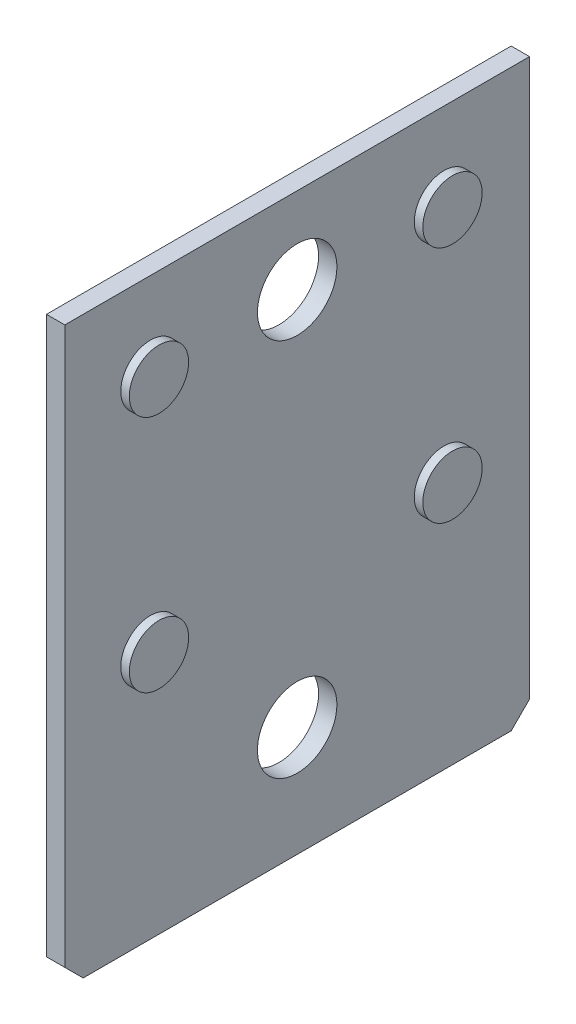
SolidWorks part; units mm, degrees
ref_plane "Front Plane" through (0, 0, 0) normal (0, 0, 1) x (1, 0, 0)
ref_plane "Top Plane" through (0, 0, 0) normal (0, 1, 0) x (1, 0, 0)
ref_plane "Right Plane" through (0, 0, 0) normal (1, 0, 0) x (0, 0, -1)
sketch "Sketch1" plane through (0, 0, 0) normal (1, 0, 0) x (0, 0, -1)
  line L1 (-19, 0) -> (19, 0)
  line L2 (-19, 0) -> (-19, 47)
  line L3 (-19, 47) -> (19, 47)
  line L4 (19, 0) -> (19, 47)
  point P4 (0, 40)
  point P6 (0, -73)
  dimension "FIX_1" = 38
  dimension "KSS_1" = 40
  dimension "FIX_2" = 7
  dimension "H" = 120
extrude "Boss-Extrude1" add sketch "Sketch1" along normal blind 1.5
sketch "Sketch2" plane through (1.5, 0, 0) normal (1, 0, 0) x (0, 0, -1)
  circle A0 centre (0, 9) radius 3.25
  circle A1 centre (0, 40) radius 3.25
  point P2 (0, 40)
  dimension "FIX_4" = 6.5
  dimension "FIX_5" = 9
  dimension "KSS_2" = 40
extrude "Cut-Extrude1" cut sketch "Sketch2" against normal through all
sketch "Sketch3" plane through (0, 0, 0) normal (-1, 0, 0) x (0, 0, 1)
  line L0 (-12, 40) -> (12, 40) construction
  circle A0 centre (-12, 40) radius 2.425
  circle A1 centre (12, 40) radius 2.425
  circle A2 centre (-12, 20.5) radius 2.425
  circle A3 centre (12, 20.5) radius 2.425
  dimension "FIX_6" = 4.85
  dimension "FIX_7" = 24
  dimension "FIX_8" = 20.5
extrude "Cut-Extrude2" cut sketch "Sketch3" against normal blind 0.7
sketch "Sketch4" plane through (1.5, 0, 0) normal (1, 0, 0) x (0, 0, -1)
  line L0 (-12, 40) -> (12, 40) construction
  circle A0 centre (-12, 40) radius 2.425
  circle A1 centre (12, 40) radius 2.425
  circle A2 centre (-12, 20.5) radius 2.425
  circle A3 centre (12, 20.5) radius 2.425
  dimension "FIX_11" = 4.85
  dimension "FIX_10" = 24
  dimension "FIX_12" = 20.5
extrude "Boss-Extrude2" add sketch "Sketch4" along normal blind 0.7
chamfer "Chamfer1" distance 1.5 2 edges at (0.75, 0, -19) (0.75, 0, 19)
equation "\"KSS_1@Sketch1\" = \"H@Sketch1\" - 80"
equation "\"KSS_2@Sketch2\"= \"H@Sketch1\" - 80"
